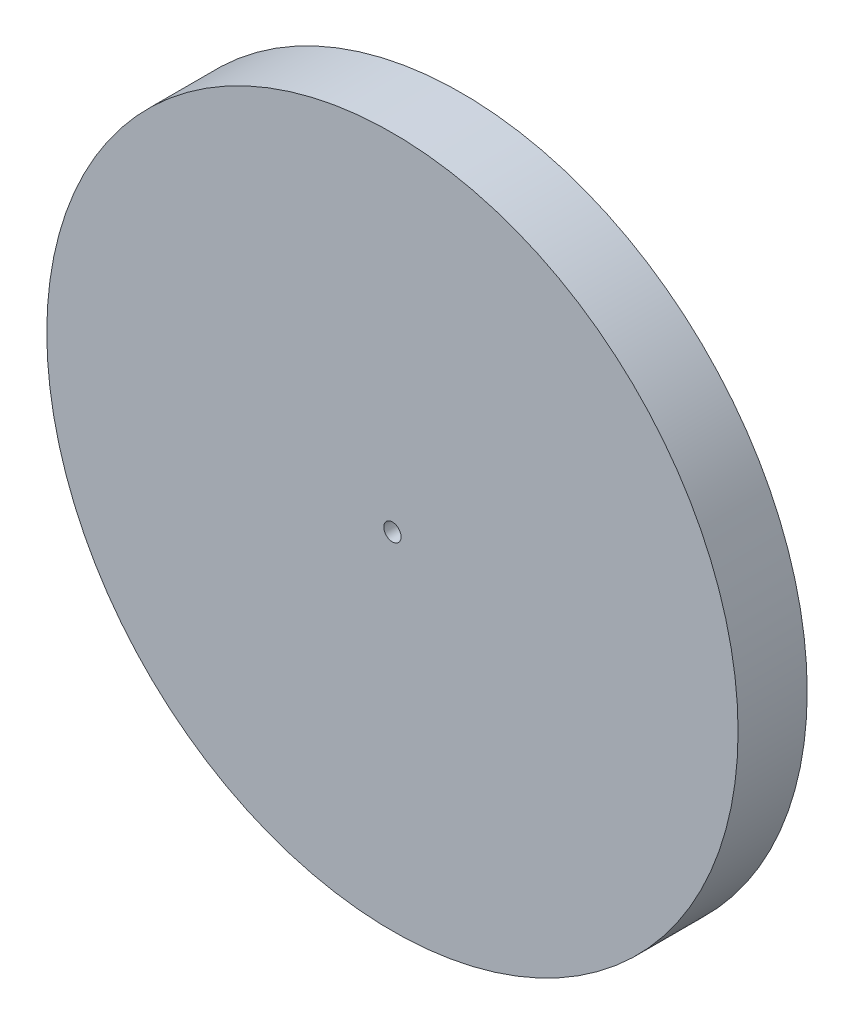
SolidWorks part; units mm, degrees
ref_plane "Front Plane" through (0, 0, 0) normal (0, 0, 1) x (1, 0, 0)
ref_plane "Top Plane" through (0, 0, 0) normal (0, 1, 0) x (1, 0, 0)
ref_plane "Right Plane" through (0, 0, 0) normal (1, 0, 0) x (0, 0, -1)
sketch "Sketch1" plane through (0, 0, 0) normal (0, 0, 1) x (1, 0, 0)
  circle A0 centre (-20.5221, 15.0559) radius 127
  circle A1 centre (-20.5221, 15.0559) radius 3.175
extrude "Boss-Extrude3" add sketch "Sketch1" along normal blind 25.4
sketch "Sketch2" plane through (0, 0, 0) normal (0, 0, -1) x (-1, 0, 0)
  circle A0 centre (20.5221, 15.0559) radius 6.35
extrude "Cut-Extrude1" cut sketch "Sketch2" against normal blind 7.62
